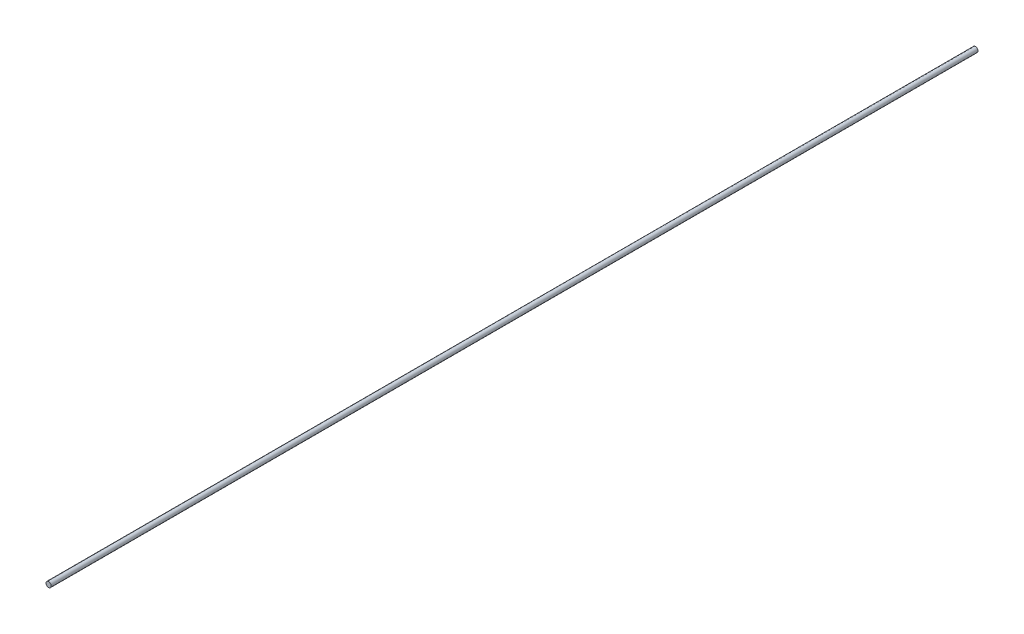
SolidWorks part; units mm, degrees
material "AISI 1020"
ref_plane "Plano frontal" through (0, 0, 0) normal (0, 0, 1) x (1, 0, 0)
ref_plane "Plano superior" through (0, 0, 0) normal (0, 1, 0) x (1, 0, 0)
ref_plane "Plano direito" through (0, 0, 0) normal (1, 0, 0) x (0, 0, -1)
sketch "Esboço1" plane through (0, 0, 0) normal (0, 0, 1) x (1, 0, 0)
  circle A0 centre (0, 0) radius 5
  dimension "D1" = 10
extrude "Ressalto-extrusão1" add sketch "Esboço1" along normal blind 1800
